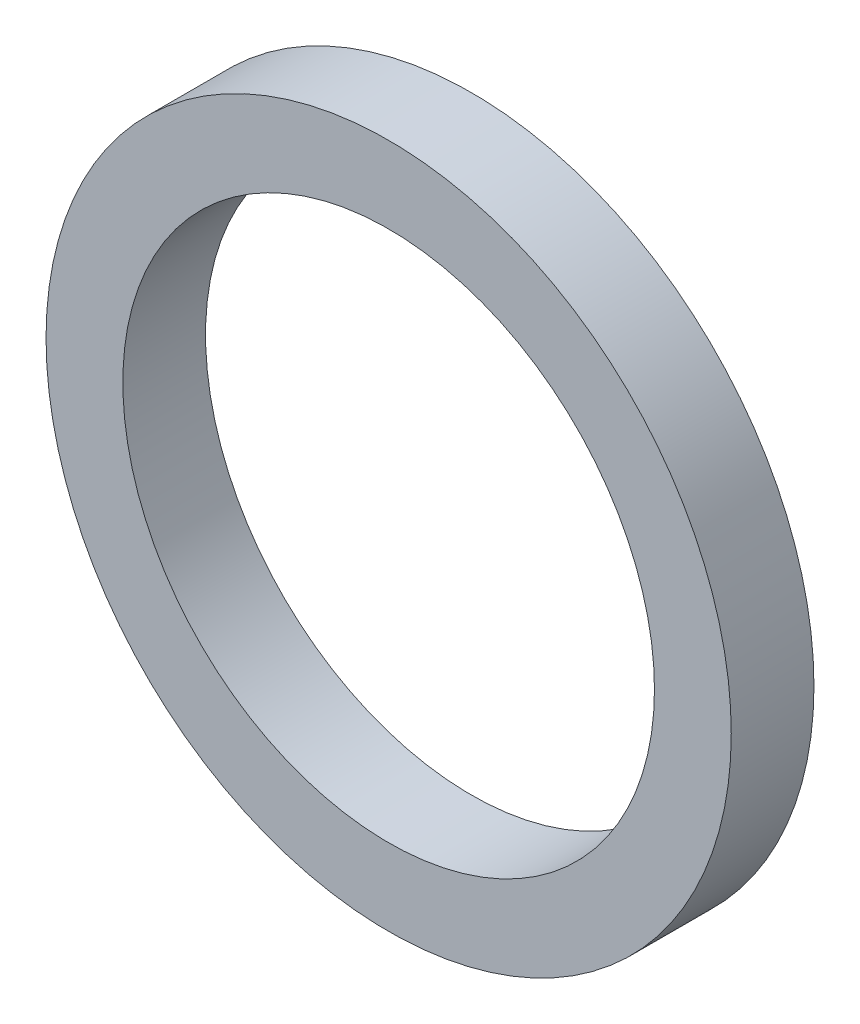
SolidWorks part; units mm, degrees
ref_plane "Ebene vorne" through (0, 0, 0) normal (0, 0, 1) x (1, 0, 0)
ref_plane "Ebene oben" through (0, 0, 0) normal (0, 1, 0) x (1, 0, 0)
ref_plane "Ebene rechts" through (0, 0, 0) normal (1, 0, 0) x (0, 0, -1)
sketch "Skizze1" plane through (0, 0, 0) normal (0, 0, 1) x (1, 0, 0)
  circle A0 centre (0, 0) radius 29
  circle A1 centre (0, 0) radius 22.5
  dimension "D1" = 58
  dimension "D2" = 45
extrude "Aufsatz-Linear austragen1" add sketch "Skizze1" along normal blind 7
